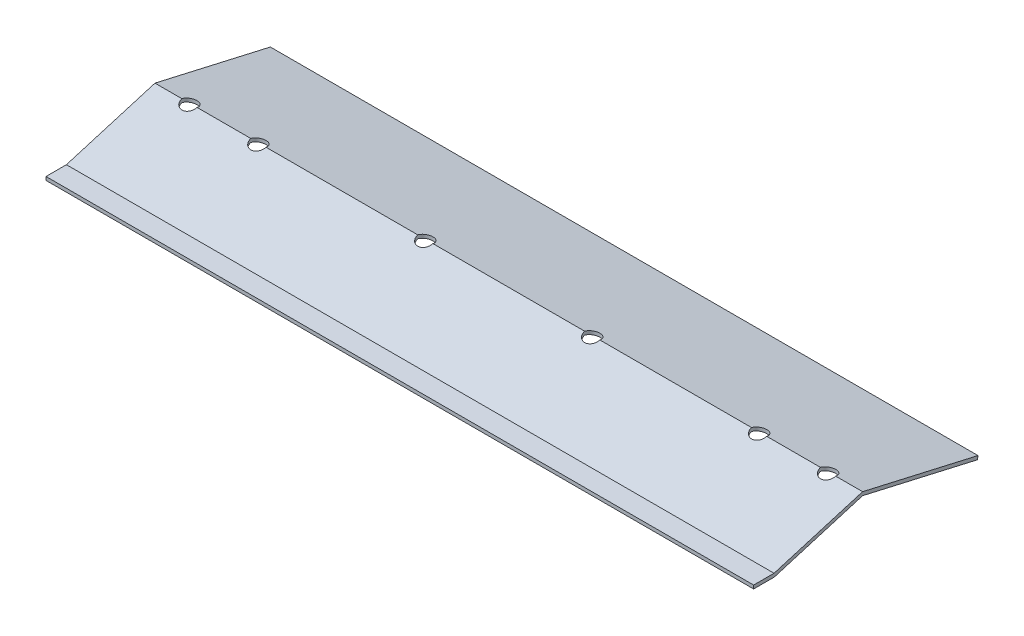
SolidWorks part; units mm, degrees
material "ASTM A36 Steel"
ref_plane "Front Plane" through (0, 0, 0) normal (0, 0, 1) x (1, 0, 0)
ref_plane "Top Plane" through (0, 0, 0) normal (0, 1, 0) x (1, 0, 0)
ref_plane "Right Plane" through (0, 0, 0) normal (1, 0, 0) x (0, 0, -1)
sketch "Sketch1" plane through (0, 0, 0) normal (1, 0, 0) x (0, 0, -1)
  line L0 (-29120.7884, 7606.8675) -> (-29091.1953, 7606.8675)
  line L1 (-29091.1953, 7606.8675) -> (-28962.7884, 7645.081)
  line L2 (-28962.7884, 7645.081) -> (-28795.4801, 7606.8017)
  line L3 (-28795.4801, 7606.8017) -> (-28796.2884, 7601.8675)
  line L4 (-28796.2884, 7601.8675) -> (-28962.7884, 7640.0143)
  line L5 (-28962.7884, 7640.0143) -> (-29090.7884, 7601.8675)
  line L6 (-29090.7884, 7601.8675) -> (-29120.7884, 7601.8675)
  line L7 (-29120.7884, 7601.8675) -> (-29120.7884, 7606.8675)
extrude "Boss-Extrude1" add sketch "Sketch1" along normal blind 1026
sketch "Sketch2" plane through (0, 0, 0) normal (0, 1, 0) x (1, 0, 0)
  line L0 (1026, -28962.7884) -> (0, -28962.7884) construction
  line L1 (0, -28795.4801) -> (0, -28962.7884) construction
  circle A0 centre (50, -28962.7884) radius 11
  circle A1 centre (150, -28962.7884) radius 11
  circle A2 centre (392, -28962.7884) radius 11
  circle A3 centre (634, -28962.7884) radius 11
  circle A4 centre (876, -28962.7884) radius 11
  circle A5 centre (976, -28962.7884) radius 11
  dimension "D1" = 22
  dimension "D2" = 22
  dimension "D3" = 50
  dimension "D4" = 100
  dimension "D5" = 22
  dimension "D6" = 22
  dimension "D7" = 22
  dimension "D8" = 22
  dimension "D9" = 242
  dimension "D10" = 242
  dimension "D11" = 242
  dimension "D12" = 100
extrude "Cut-Extrude1" cut sketch "Sketch2" against normal through all both and the other way through all
